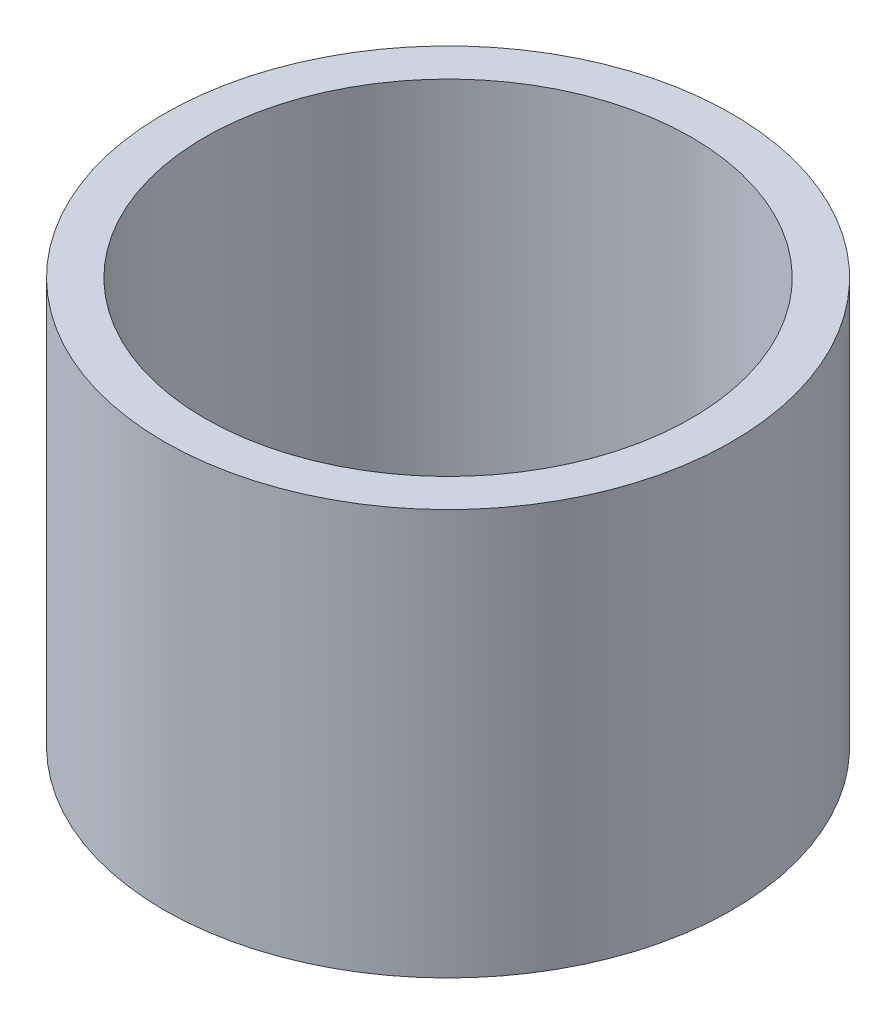
SolidWorks part; units mm, degrees
ref_plane "Front Plane" through (0, 0, 0) normal (0, 0, 1) x (1, 0, 0)
ref_plane "Top Plane" through (0, 0, 0) normal (0, 1, 0) x (1, 0, 0)
ref_plane "Right Plane" through (0, 0, 0) normal (1, 0, 0) x (0, 0, -1)
sketch "Sketch1" plane through (0, 0, 0) normal (0, 1, 0) x (1, 0, 0)
  circle A0 centre (0, 0) radius 6
  circle A1 centre (0, 0) radius 7
extrude "Boss-Extrude1" add sketch "Sketch1" along normal blind 10
